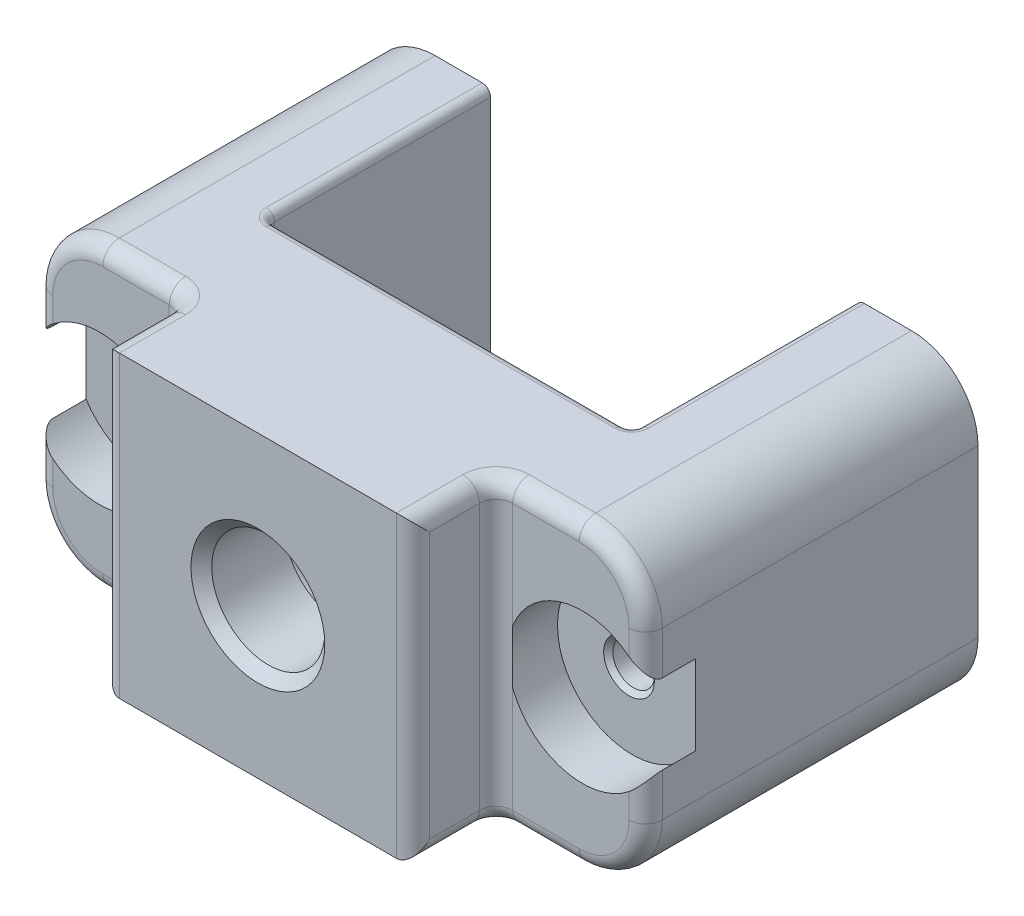
SolidWorks part; units mm, degrees
ref_plane "Front Plane" through (0, 0, 0) normal (0, 0, 1) x (1, 0, 0)
ref_plane "Top Plane" through (0, 0, 0) normal (0, 1, 0) x (1, 0, 0)
ref_plane "Right Plane" through (0, 0, 0) normal (1, 0, 0) x (0, 0, -1)
sketch "Sketch1" plane through (0, 0, 0) normal (0, 0, 1) x (1, 0, 0)
  line L0 (0, 9) -> (0, 13.2219) construction
  line L1 (-14.3348, 9) -> (14.3348, 9)
  line L2 (-18.3348, 5) -> (-18.3348, -5)
  line L3 (-14.3348, -9) -> (14.3348, -9)
  line L4 (18.3348, 5) -> (18.3348, -5)
  line L5 (-18.3348, 9) -> (18.3348, -9) construction
  line L6 (-18.3348, -9) -> (18.3348, 9) construction
  circle A0 centre (0, 0) radius 5.5
  circle A2 centre (-14.3348, 0) radius 1
  arc A3 (14.3348, 9) -> (18.3348, 5) centre (14.3348, 5) cw
  arc A4 (14.3348, -9) -> (18.3348, -5) centre (14.3348, -5) ccw
  arc A5 (-18.3348, -5) -> (-14.3348, -9) centre (-14.3348, -5) ccw
  arc A6 (-14.3348, 9) -> (-18.3348, 5) centre (-14.3348, 5) ccw
  circle A7 centre (14.3348, 0) radius 1
  dimension "D1" = 11
  dimension "D2" = 9
  dimension "D3" = 2
  dimension "D4" = 4
  dimension "D5" = 4
extrude "Boss-Extrude1" add sketch "Sketch1" along normal blind 15
sketch "Sketch3" plane through (0, 0, 15) normal (0, 0, 1) x (1, 0, 0)
  line L1 (-9.3348, 10.683) -> (-19.3342, 10.683)
  line L2 (-9.3348, 10.683) -> (-9.3348, -11.5423)
  line L3 (-9.3348, -11.5423) -> (-19.3342, -11.5423)
  line L4 (-19.3342, 10.683) -> (-19.3342, -11.5423)
  circle A1 centre (-14.3348, 0) radius 1 construction
  dimension "D1" = 5
extrude "Cut-Extrude1" cut sketch "Sketch3" against normal blind 5
fillet "Fillet1" radius 1 9 edges at (-11.8348, 9, 10) (-9.3348, 0, 10) (-11.8348, -9, 10) (-17.1632, -7.8284, 10) (-18.3348, 0, 10) (-17.1632, 7.8284, 10) (-9.3348, 9, 12.5) (-9.3348, -9, 12.5) (-9.3348, 0, 15)
mirror "Mirror1" about plane through (0, 0, 0) normal (1, 0, 0) of "Cut-Extrude1", "Fillet1"
sketch "Sketch4" plane through (0, 0, 15) normal (0, 0, 1) x (1, 0, 0)
  circle A0 centre (0, 0) radius 7.5
  dimension "D1" = 15
extrude "Boss-Extrude2" add sketch "Sketch4" against normal blind 5
sketch "Sketch5" plane through (0, 9, 0) normal (0, 1, 0) x (1, 0, 0)
  line L1 (-11, 3.5) -> (11, 3.5)
  line L2 (-11, 3.5) -> (-11, -3.5)
  line L3 (-11, -3.5) -> (11, -3.5)
  line L4 (11, 3.5) -> (11, -3.5)
  line L5 (-11, 3.5) -> (11, -3.5) construction
  line L6 (-11, -3.5) -> (11, 3.5) construction
  line L7 (14.3348, 0) -> (-14.3348, 0) construction
  point P0 (0, 0)
  dimension "D1" = 22
  dimension "D2" = 3.5
extrude "Cut-Extrude2" cut sketch "Sketch5" against normal through all
sketch "Sketch6" plane through (0, 0, 15) normal (0, 0, 1) x (1, 0, 0)
  circle A0 centre (0, 0) radius 3
  dimension "D1" = 6
extrude "Cut-Extrude3" cut sketch "Sketch6" against normal through all
sketch "Sketch7" plane through (0, 0, 10) normal (0, 0, 1) x (1, 0, 0)
  circle A0 centre (-14.5304, 0) radius 4.5
  circle A1 centre (14.5304, 0) radius 4.5
  dimension "D1" = 9
  dimension "D2" = 9
extrude "Cut-Extrude8" cut sketch "Sketch7" against normal blind 3
fillet "Fillet3" radius 0.5 8 edges at (-11, 0, 3.5) (0, -9, 3.5) (11, 0, 3.5) (0, 9, 3.5) (-11, -9, 1.75) (11, -9, 1.75) (11, 9, 1.75) (-11, 9, 1.75)
fillet "Fillet2" radius 0.5 1 edges at (5.5, 0, 10)
sketch "Sketch8" plane through (0, 0, 0) normal (0, 0, -1) x (-1, 0, 0)
  line L4 (11, 8.5) -> (11, -8.5)
  line L5 (11.5, -9) -> (14.3348, -9)
  line L6 (18.3348, -5) -> (18.3348, 5)
  line L7 (14.3348, 9) -> (11.5, 9)
  line L8 (11, 8.5) -> (11, -8.5)
  line L9 (11.5, -9) -> (14.3348, -9)
  line L10 (18.3348, -5) -> (18.3348, 5)
  line L11 (14.3348, 9) -> (11.5, 9)
  line L12 (-14.3348, -9) -> (-11.5, -9)
  line L13 (-11, -8.5) -> (-11, 8.5)
  line L14 (-11.5, 9) -> (-14.3348, 9)
  line L15 (-18.3348, 5) -> (-18.3348, -5)
  line L16 (-14.3348, -9) -> (-11.5, -9)
  line L17 (-11, -8.5) -> (-11, 8.5)
  line L18 (-11.5, 9) -> (-14.3348, 9)
  line L19 (-18.3348, 5) -> (-18.3348, -5)
  circle A0 centre (14.3348, 0) radius 1 construction
  circle A1 centre (-14.3348, 0) radius 1
  circle A2 centre (-14.3348, 0) radius 1
  circle A3 centre (14.3348, 0) radius 1
  arc A4 (11, -8.5) -> (11.5, -9) centre (11.5, -8.5) ccw
  arc A5 (14.3348, -9) -> (18.3348, -5) centre (14.3348, -5) ccw
  arc A6 (18.3348, 5) -> (14.3348, 9) centre (14.3348, 5) ccw
  arc A7 (11.5, 9) -> (11, 8.5) centre (11.5, 8.5) ccw
  arc A8 (11, -8.5) -> (11.5, -9) centre (11.5, -8.5) ccw
  arc A9 (14.3348, -9) -> (18.3348, -5) centre (14.3348, -5) ccw
  arc A10 (18.3348, 5) -> (14.3348, 9) centre (14.3348, 5) ccw
  arc A11 (11.5, 9) -> (11, 8.5) centre (11.5, 8.5) ccw
  arc A16 (-11.5, -9) -> (-11, -8.5) centre (-11.5, -8.5) ccw
  arc A17 (-11, 8.5) -> (-11.5, 9) centre (-11.5, 8.5) ccw
  arc A18 (-14.3348, 9) -> (-18.3348, 5) centre (-14.3348, 5) ccw
  arc A19 (-18.3348, -5) -> (-14.3348, -9) centre (-14.3348, -5) ccw
  arc A20 (-11.5, -9) -> (-11, -8.5) centre (-11.5, -8.5) ccw
  arc A21 (-11, 8.5) -> (-11.5, 9) centre (-11.5, 8.5) ccw
  arc A22 (-14.3348, 9) -> (-18.3348, 5) centre (-14.3348, 5) ccw
  arc A23 (-18.3348, -5) -> (-14.3348, -9) centre (-14.3348, -5) ccw
  dimension "D1" = 0
  dimension "D2" = 0
  dimension "D3" = 0
extrude "Boss-Extrude3" add sketch "Sketch8" along normal blind 10
hole_wizard "M8x1.25 Tapped Hole1" positions "3DSketch1" profile "Sketch9" tap size "M8x1.25" standard "ANSI Metric" end condition through all
sketch3d "3DSketch1"
  line L0 (0, 0, 10) -> (0, 0, 15) construction
  point P0 (0, 0, 15)
sketch "Sketch9" plane through (0, 0, 15) normal (1, 0, 0) x (0, -1, 0)
  line L0 (0, 0) -> (0, 25)
  line L1 (0, 25) -> (3.4, 25)
  line L2 (3.4, 25) -> (3.4, 0.625)
  line L3 (3.4, 0.625) -> (4.025, 0)
  line L5 (4.025, 0) -> (0, 0)
  line L6 (-3.4, 0.625) -> (-4.025, 0) construction
  line L11 (0, -6.35) -> (0, 107.95) construction
  dimension "Thru Tap Drill Dia." = 6.8
  dimension "Thru Tap Drill Depth" = 25
  dimension "Near C'Sink Dia." = 8.05
  dimension "Near C'Sink Angle" = 90
cosmetic thread "Hole Thread1" parameters "D2"=8
fillet "Fillet4" radius 0.5 1 edges at (5.5, 0, 3.5)
hole_wizard "M3x0.5 Tapped Hole1" positions "3DSketch2" profile "Sketch10" tap size "M3x0.5" standard "ANSI Metric" end condition through all
sketch3d "3DSketch2"
  line L0 (-14.3348, 0, 7) -> (-14.3348, 0, -10) construction
  line L1 (14.3348, 0, 7) -> (14.3348, 0, -10) construction
  point P0 (-14.3348, 0, 7)
  point P4 (14.3348, 0, 7)
sketch "Sketch10" plane through (-14.3348, 0, 7) normal (1, 0, 0) x (0, -1, 0)
  line L0 (0, 0) -> (0, 17)
  line L1 (0, 17) -> (1.25, 17)
  line L2 (1.25, 17) -> (1.25, 0.275)
  line L3 (1.25, 0.275) -> (1.525, 0)
  line L5 (1.525, 0) -> (0, 0)
  line L6 (-1.25, 0.275) -> (-1.525, 0) construction
  line L11 (0, -6.35) -> (0, 107.95) construction
  dimension "Thru Tap Drill Dia." = 2.5
  dimension "Thru Tap Drill Depth" = 17
  dimension "Near C'Sink Dia." = 3.05
  dimension "Near C'Sink Angle" = 90
cosmetic thread "Hole Thread2" parameters "D2"=3
cosmetic thread "Hole Thread3" parameters "D2"=3
